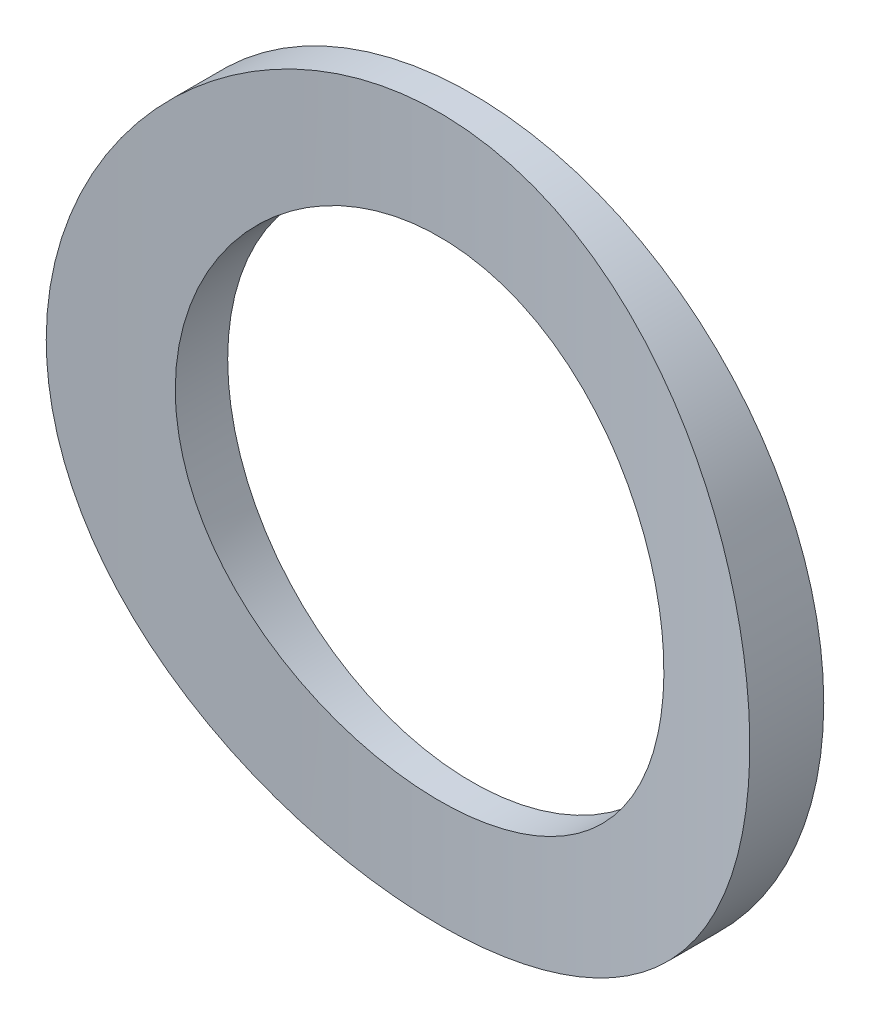
SolidWorks part; units mm, degrees
material "PTFE (general)"
ref_plane "Front Plane" through (0, 0, 0) normal (0, 0, 1) x (1, 0, 0)
ref_plane "Top Plane" through (0, 0, 0) normal (0, 1, 0) x (1, 0, 0)
ref_plane "Right Plane" through (0, 0, 0) normal (1, 0, 0) x (0, 0, -1)
sketch "Sketch1" plane through (0, 0, 0) normal (0, 0, 1) x (1, 0, 0)
  circle A0 centre (0, 0) radius 10.8
  circle A1 centre (0, 0) radius 7.5
  dimension "D1" = 21.6
  dimension "D2" = 15
extrude "Boss-Extrude1" add sketch "Sketch1" along normal blind 30
sketch "Sketch2" plane through (0, 0, 0) normal (0, 1, 0) x (1, 0, 0)
  line L0 (10.8, 0) -> (-10.8, 0) construction
  circle A0 centre (0, -47.53) radius 46.53
  dimension "D1" = 93.06
  dimension "D2" = 47.53
extrude "Cut-Extrude1" cut sketch "Sketch2" against normal through all both and the other way through all
